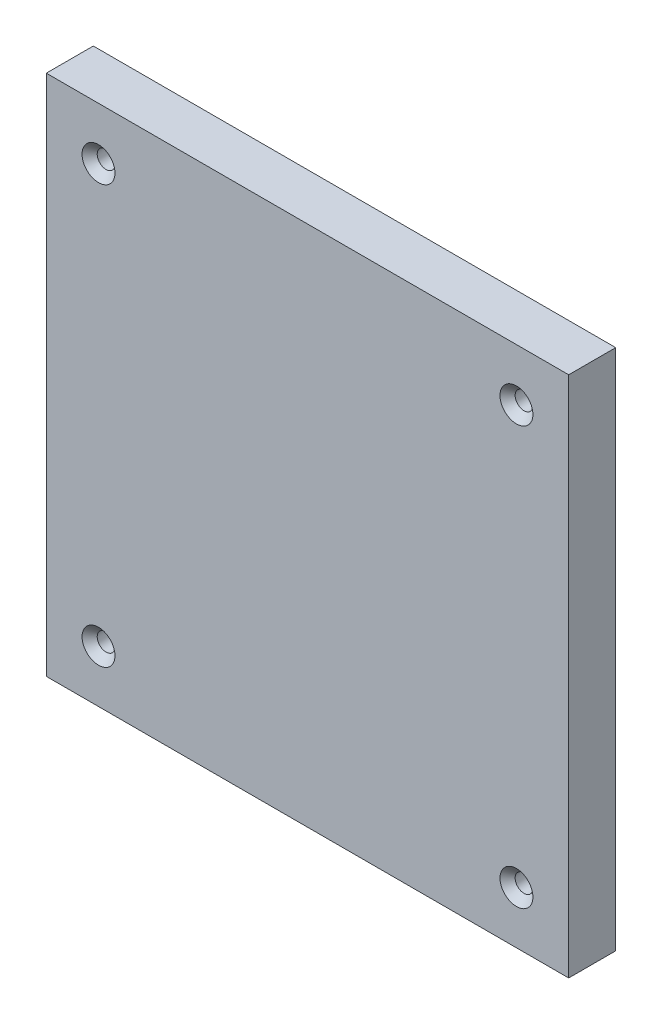
SolidWorks part; units mm, degrees
material "Birch Plywood"
ref_plane "前基準面" through (0, 0, 0) normal (0, 0, 1) x (1, 0, 0)
ref_plane "上基準面" through (0, 0, 0) normal (0, 1, 0) x (1, 0, 0)
ref_plane "右基準面" through (0, 0, 0) normal (1, 0, 0) x (0, 0, -1)
sketch "草圖1" plane through (0, 0, 0) normal (0, 0, 1) x (1, 0, 0)
  line L1 (-50, 50) -> (50, 50)
  line L2 (-50, 50) -> (-50, -50)
  line L3 (-50, -50) -> (50, -50)
  line L4 (50, 50) -> (50, -50)
  line L5 (-50, 50) -> (50, -50) construction
  line L6 (-50, -50) -> (50, 50) construction
  point P0 (0, 0)
  dimension "D1" = 100
  dimension "D2" = 100
extrude "填料-伸長1" add sketch "草圖1" along normal blind 9
sketch "草圖2" plane through (0, 0, 9) normal (0, 0, 1) x (1, 0, 0)
  line L4 (50, -50) -> (50, 50)
  line L5 (50, 50) -> (-50, 50)
  line L6 (-50, 50) -> (-50, -50)
  line L7 (-50, -50) -> (50, -50)
  line L8 (50, -50) -> (50, 50)
  line L9 (50, 50) -> (-50, 50)
  line L10 (-50, 50) -> (-50, -50)
  line L11 (-50, -50) -> (50, -50)
  point P2 (-40, 40)
  point P4 (40, 40)
  point P6 (40, -40)
  point P7 (-40, -40)
  point P8 (0, 0)
  point P9 (0, 0)
  point P10 (0, 0)
  point P11 (0, 0)
  point P12 (0, 0)
  dimension "D2" = 10
  dimension "D3" = 10
  dimension "D4" = 10
  dimension "D5" = 10
  dimension "D6" = 10
  dimension "D1" = 0
hole_wizard "M3 平頭機械螺釘的錐孔1" positions "3D草圖2" profile "草圖4" countersink size "M3" standard "Ansi Metric" end condition through all
sketch3d "3D草圖2"
  point P0 (-40, 40, 9)
  point P3 (40, 40, 9)
  point P6 (40, -40, 9)
  point P9 (-40, -40, 9)
sketch "草圖4" plane through (-40, 40, 9) normal (1, 0, 0) x (0, -1, 0)
  line L0 (0, 0) -> (0, 9)
  line L1 (0, 9) -> (1.725, 9)
  line L2 (1.7, 8.975) -> (1.7, 1.45)
  line L3 (1.7, 1.45) -> (3.15, 0)
  line L5 (3.15, 0) -> (0, 0)
  line L6 (-1.7, 1.45) -> (-3.15, 0) construction
  line L7 (1.725, 9) -> (1.7, 8.975)
  line L8 (-1.725, 9) -> (-1.7, 8.975) construction
  line L11 (0, -6.35) -> (0, 107.95) construction
  dimension "貫穿孔直徑" = 3.4
  dimension "貫穿孔深度" = 9
  dimension "近端錐孔直徑" = 6.3
  dimension "近端錐孔角度" = 90
  dimension "遠端錐孔直徑" = 3.45
  dimension "遠端錐孔角度" = 90
